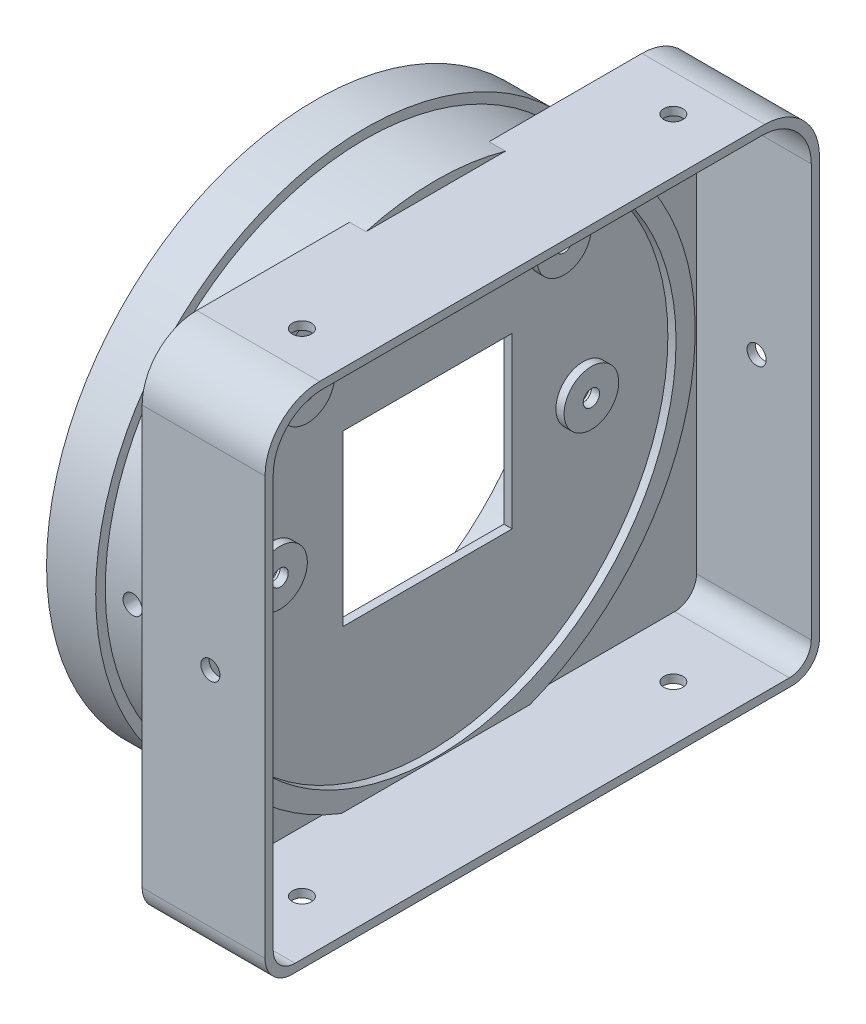
SolidWorks part; units mm, degrees
ref_plane "前视基准面" through (0, 0, 0) normal (0, 0, 1) x (1, 0, 0)
ref_plane "上视基准面" through (0, 0, 0) normal (0, 1, 0) x (1, 0, 0)
ref_plane "右视基准面" through (0, 0, 0) normal (1, 0, 0) x (0, 0, -1)
sketch "草图1" plane through (0, 0, 0) normal (1, 0, 0) x (0, 0, -1)
  line L0 (1.5, 1.5) -> (1.5, 90)
  line L1 (0, 0) -> (101.5, 0)
  line L2 (0, 0) -> (0, 91.5)
  line L3 (0, 91.5) -> (101.5, 91.5)
  line L4 (101.5, 0) -> (101.5, 91.5)
  line L5 (1.5, 90) -> (100, 90)
  line L6 (100, 1.5) -> (100, 90)
  line L7 (1.5, 1.5) -> (100, 1.5)
  dimension "D1" = 101.5
  dimension "D2" = 91.5
  dimension "D3" = 1.5
extrude "凸台-拉伸1" add sketch "草图1" along normal blind 21
sketch "草图2" plane through (0, 0, 0) normal (-1, 0, 0) x (0, 0, 1)
  line L0 (-50.75, 90) -> (-50.75, -4.3889) construction
  line L1 (-101.5, 91.5) -> (0, 91.5)
  line L2 (-101.5, 91.5) -> (-101.5, 0)
  line L3 (-101.5, 0) -> (0, 0)
  line L4 (0, 91.5) -> (0, 0)
  line L5 (-100, 90) -> (-1.5, 90) construction
  line L7 (-1.5, 1.5) -> (-100, 1.5) construction
  line L9 (-66.25, 60.5) -> (-35.25, 60.5)
  line L10 (-66.25, 60.5) -> (-66.25, 29.5)
  line L11 (-66.25, 29.5) -> (-35.25, 29.5)
  line L12 (-35.25, 60.5) -> (-35.25, 29.5)
  circle A2 centre (-27.25, 71.5) radius 1.5
  circle A3 centre (-22.25, 44.5) radius 1.5
  circle A4 centre (-79.25, 44.5) radius 1.5
  circle A5 centre (-74.25, 71.5) radius 1.5
  point P24 (-50.75, 60.5)
  point P25 (-50.75, 58.5133)
  dimension "D1" = 3
  dimension "D2" = 3
  dimension "D5" = 57
  dimension "D3" = 47
  dimension "D6" = 43
  dimension "D4" = 70
  dimension "D7" = 31
  dimension "D8" = 31
  dimension "D9" = 28
extrude "凸台-拉伸2" add sketch "草图2" along normal blind 1.5
sketch "草图3" plane through (0, 0, 0) normal (0, 0, 1) x (1, 0, 0)
  line L0 (11, 95.0538) -> (11, -6.5657) construction
  line L3 (-1.5, 45.75) -> (35.7467, 45.75) construction
  line L4 (-1.5, 0) -> (-1.5, 91.5) construction
  line L5 (21, 91.5) -> (21, 0) construction
  circle A1 centre (11, 45.75) radius 1.75
  dimension "D1" = 10
  dimension "D2" = 3.5
extrude "切除-拉伸1" cut sketch "草图3" against normal through all
sketch "草图4" plane through (0, 91.5, 0) normal (0, 1, 0) x (1, 0, 0)
  line L0 (11, 109.1455) -> (11, -1.1086) construction
  line L3 (21, 50.75) -> (-1.5, 50.75) construction
  line L4 (21, 101.5) -> (21, 0) construction
  line L5 (-1.5, 0) -> (-1.5, 101.5) construction
  circle A1 centre (11, 16.75) radius 1.75
  circle A2 centre (11, 84.75) radius 1.75
  dimension "D1" = 68
  dimension "D2" = 3.5
  dimension "D3" = 10
extrude "切除-拉伸2" cut sketch "草图4" against normal through all
fillet "圆角1" radius 9 2 edges at (10.5, 90, -1.5) (10.5, 90, -100)
fillet "圆角2" radius 10 2 edges at (9.75, 91.5, -101.5) (9.75, 91.5, 0)
fillet "圆角3" radius 4 2 edges at (10.5, 1.5, -1.5) (10.5, 1.5, -100)
fillet "圆角4" radius 5 2 edges at (9.75, 0, -101.5) (9.75, 0, 0)
sketch "草图5" plane through (-1.5, 0, 0) normal (-1, 0, 0) x (0, 0, 1)
  line L0 (-50.75, 0) -> (-50.75, 91.5) construction
  line L1 (-96.5, 0) -> (-5, 0) construction
  line L2 (-10, 91.5) -> (-91.5, 91.5) construction
  line L4 (-73.25, 66) -> (-28.25, 66)
  line L5 (-73.25, 66) -> (-73.25, 20)
  line L6 (-73.25, 20) -> (-28.25, 20)
  line L7 (-28.25, 66) -> (-28.25, 20)
  circle A0 centre (-50.75, 45.75) radius 47.5
  circle A5 centre (-27.25, 71.5) radius 1.5
  circle A6 centre (-22.25, 44.5) radius 1.5
  circle A7 centre (-79.25, 44.5) radius 1.5
  circle A8 centre (-74.25, 71.5) radius 1.5
  circle A9 centre (-79.25, 44.5) radius 1.5 construction
  circle A10 centre (-74.25, 71.5) radius 1.5 construction
  circle A11 centre (-27.25, 71.5) radius 1.5 construction
  circle A12 centre (-22.25, 44.5) radius 1.5 construction
  point P24 (-50.75, 66)
  point P25 (-50.75, 64.4825)
  dimension "D1" = 95
  dimension "D6" = 45
  dimension "D7" = 46
  dimension "D8" = 20
extrude "凸台-拉伸3" add sketch "草图5" against normal blind 3
sketch "草图6" plane through (1.5, 0, 0) normal (1, 0, 0) x (0, 0, -1)
  circle A0 centre (50.75, 45.75) radius 47.5
  circle A1 centre (50.75, 45.75) radius 43.5
  arc A2 (68.0181, 1.5) -> (68.0181, 90) centre (50.75, 45.75) ccw construction
  dimension "D1" = 4
extrude "凸台-拉伸4" add sketch "草图6" against normal blind 13
sketch "草图7" plane through (-11.5, 0, 0) normal (-1, 0, 0) x (0, 0, 1)
  circle A0 centre (-50.75, 45.75) radius 49.25
  circle A1 centre (-50.75, 45.75) radius 43.5
  circle A2 centre (-50.75, 45.75) radius 43.5 construction
  dimension "D1" = 98.5
extrude "凸台-拉伸5" add sketch "草图7" along normal blind 9
sketch "草图8" plane through (1.5, 0, 0) normal (1, 0, 0) x (0, 0, -1)
  circle A0 centre (50.75, 45.75) radius 44
  circle A1 centre (74.25, 71.5) radius 5
  circle A2 centre (79.25, 44.5) radius 5
  circle A3 centre (22.25, 44.5) radius 5
  circle A4 centre (27.25, 71.5) radius 5
  dimension "D1" = 88
  dimension "D2" = 10
  dimension "D3" = 10
  dimension "D4" = 10
  dimension "D5" = 10
extrude "切除-拉伸3" cut sketch "草图8" against normal blind 1.5
sketch "草图9" plane through (0, 0, 0) normal (0, 0, 1) x (1, 0, 0)
  line L0 (-1.5, 45.75) -> (-11.5, 45.75) construction
  line L1 (-1.5, 91.5) -> (-1.5, 0) construction
  line L2 (-11.5, -1.75) -> (-11.5, 93.25) construction
  circle A0 centre (-6.5, 45.75) radius 1.75
  dimension "D1" = 3.5
extrude "切除-拉伸4" cut sketch "草图9" against normal through all
sketch "草图10" plane through (-1.5, 0, 0) normal (-1, 0, 0) x (0, 0, 1)
  circle A0 centre (-74.25, 71.5) radius 3
  circle A1 centre (-27.25, 71.5) radius 3
  circle A2 centre (-22.25, 44.5) radius 3
  circle A3 centre (-79.25, 44.5) radius 3
  dimension "D1" = 6
  dimension "D2" = 6
  dimension "D3" = 6
  dimension "D4" = 6
extrude "切除-拉伸5" cut sketch "草图10" against normal blind 1.5
